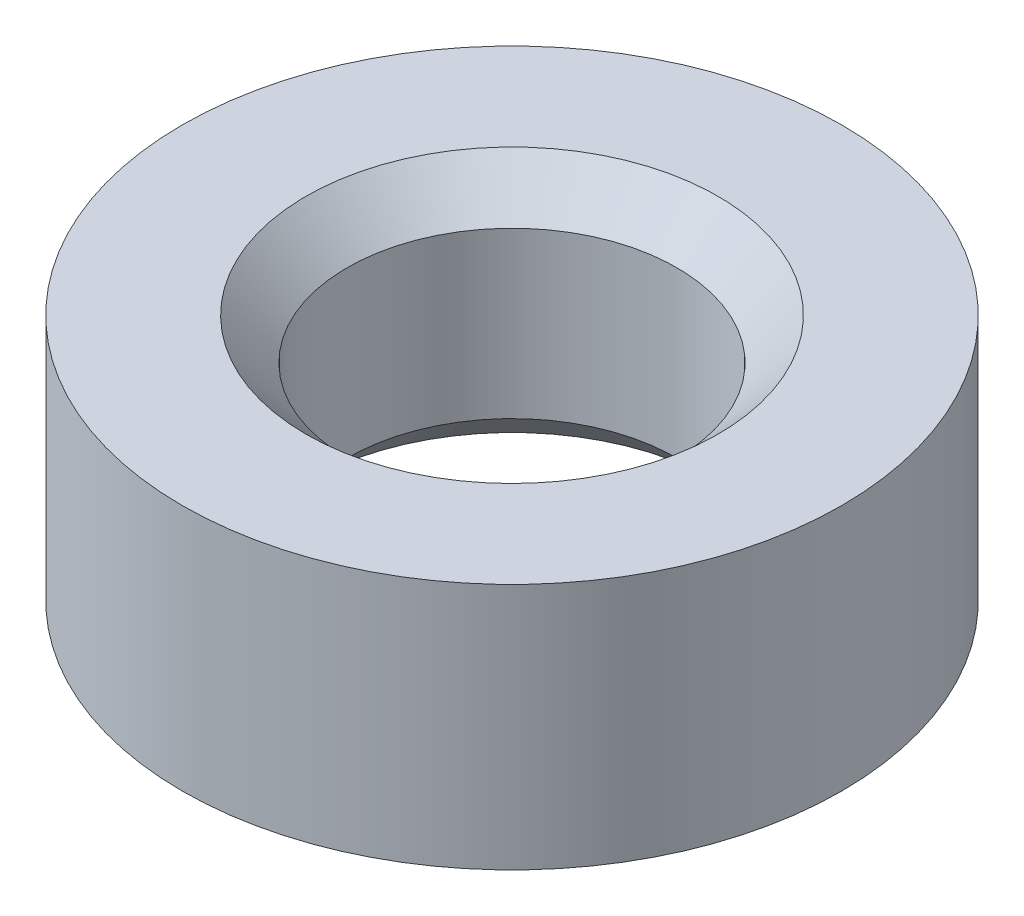
SolidWorks part; units mm, degrees
ref_plane "Front Plane" through (0, 0, 0) normal (0, 0, 1) x (1, 0, 0)
ref_plane "Top Plane" through (0, 0, 0) normal (0, 1, 0) x (1, 0, 0)
ref_plane "Right Plane" through (0, 0, 0) normal (1, 0, 0) x (0, 0, -1)
sketch "Sketch1" plane through (0, 0, 0) normal (0, 1, 0) x (1, 0, 0)
  circle A0 centre (0, 0) radius 4
  dimension "D1" = 8
extrude "Boss-Extrude1" add sketch "Sketch1" along normal blind 3
sketch "Sketch2" plane through (0, 3, 0) normal (0, 1, 0) x (1, 0, 0)
  circle A0 centre (0, 0) radius 2
  dimension "D1" = 4
extrude "Cut-Extrude1" cut sketch "Sketch2" against normal through all
chamfer "Chamfer2" distance 0.5 angle 45 2 edges at (0, 3, 2) (0, 0, 2)
